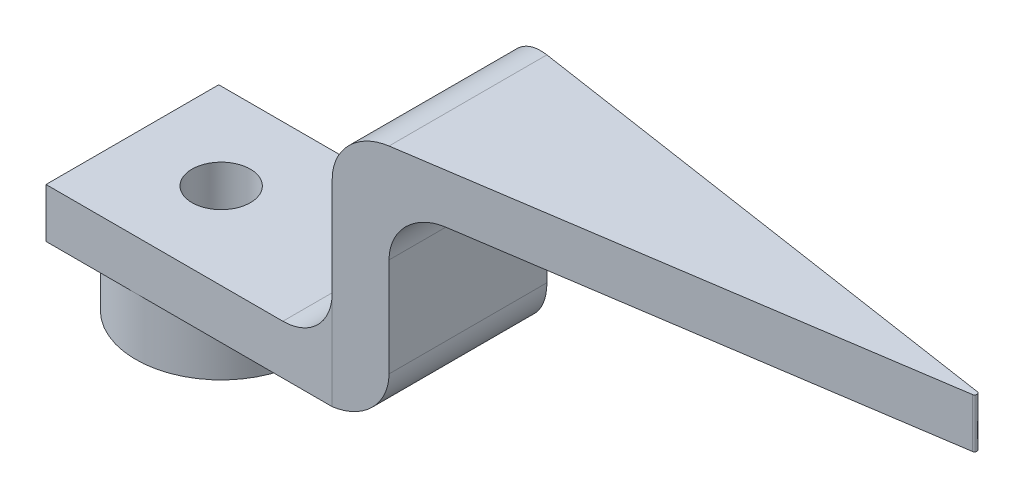
SolidWorks part; units mm, degrees
material "ABS"
ref_plane "Front Plane" through (0, 0, 0) normal (0, 0, 1) x (1, 0, 0)
ref_plane "Top Plane" through (0, 0, 0) normal (0, 1, 0) x (1, 0, 0)
ref_plane "Right Plane" through (0, 0, 0) normal (1, 0, 0) x (0, 0, -1)
sketch "Sketch1" plane through (0, 0, 0) normal (0, 0, 1) x (1, 0, 0)
  line L0 (39.624, 10.16) -> (12.7, 10.16)
  line L1 (12.7, 10.16) -> (12.7, 0)
  line L2 (12.7, 0) -> (0, 0)
  line L3 (0, 0) -> (-4.572, 0)
  dimension "D1" = 26.924
  dimension "D2" = 10.16
  dimension "D3" = 12.7
  dimension "D4" = 4.572
extrude "Extrude-Thin1" add sketch "Sketch1" along normal mid plane 8.89 thin
sketch "Sketch2" plane through (0, 12.7, 0) normal (0, 1, 0) x (1, 0, 0)
  line L0 (10.16, 4.445) -> (38.7916, 0.1256)
  line L3 (39.624, -4.445) -> (39.624, 4.445) construction
  line L5 (38.7916, -0.1256) -> (10.16, -4.445)
  line L6 (10.16, -4.445) -> (39.624, -4.445)
  line L7 (39.624, -4.445) -> (39.624, 4.445)
  line L8 (39.624, 4.445) -> (10.16, 4.445) construction
  line L9 (39.624, 4.445) -> (10.16, 4.445)
  arc A0 (38.7916, -0.1256) -> (38.7916, 0.1256) centre (38.7726, 0) ccw
  point P12 (39.624, 0)
  line M2 (39.624, 4.445) -> (10.16, 4.445)
  line M4 (10.16, -4.445) -> (39.624, -4.445)
  line M5 (39.624, -4.445) -> (39.624, 4.445)
  dimension "D1" = 0.127
extrude "Cut-Extrude1" cut sketch "Sketch2" against normal through all contours L5 M5 M4 | L0 M2 M5
fillet "Fillet1" radius 2.54 4 edges at (10.16, 2.54, 0) (12.7, 10.16, 0) (12.7, 0, 0) (10.16, 12.7, 0)
sketch "Sketch3" plane through (0, 2.54, 0) normal (0, 1, 0) x (1, 0, 0)
  circle A0 centre (0, 0) radius 1.5
  dimension "D1" = 3
extrude "Cut-Extrude2" cut sketch "Sketch3" against normal through all
sketch "Sketch4" plane through (0, 0, 0) normal (0, -1, 0) x (1, 0, 0)
  circle A0 centre (0, 0) radius 4.4
  dimension "D1" = 8.8
extrude "Boss-Extrude1" add sketch "Sketch4" along normal blind 3
sketch "Sketch5" plane through (0, -3, 0) normal (0, -1, 0) x (1, 0, 0)
  line L0 (0.1143, 2.4894) -> (0.0406, 2.3567)
  line L1 (0.0406, 2.3567) -> (-0.0406, 2.3567)
  line L2 (-0.0406, 2.3567) -> (-0.1143, 2.4894)
  line L3 (0, 2.3567) -> (0, 0) construction
  line L4 (0.3071, 2.3375) -> (0.2526, 2.4792)
  line L5 (0.3875, 2.3262) -> (0.3071, 2.3375)
  line L6 (0.4406, 2.4527) -> (0.3875, 2.3262)
  line L7 (0.6294, 2.2721) -> (0.5951, 2.4199)
  line L8 (0.7075, 2.2497) -> (0.6294, 2.2721)
  line L9 (0.7776, 2.3676) -> (0.7075, 2.2497)
  line L10 (0.9395, 2.1624) -> (0.9261, 2.3135)
  line L11 (1.0137, 2.1293) -> (0.9395, 2.1624)
  line L12 (1.0996, 2.2363) -> (1.0137, 2.1293)
  line L13 (1.2313, 2.0106) -> (1.2391, 2.1621)
  line L14 (1.3001, 1.9675) -> (1.2313, 2.0106)
  line L15 (1.4001, 2.0615) -> (1.3001, 1.9675)
  line L16 (1.4991, 1.8196) -> (1.5279, 1.9686)
  line L17 (1.5613, 1.7674) -> (1.4991, 1.8196)
  line L18 (1.6734, 1.8466) -> (1.5613, 1.7674)
  line L19 (1.7378, 1.5933) -> (1.7871, 1.7368)
  line L20 (1.7921, 1.5329) -> (1.7378, 1.5933)
  line L21 (1.9141, 1.5957) -> (1.7921, 1.5329)
  line L22 (1.9426, 1.3359) -> (2.0114, 1.4712)
  line L23 (1.988, 1.2686) -> (1.9426, 1.3359)
  line L24 (2.1175, 1.3138) -> (1.988, 1.2686)
  line L25 (2.1096, 1.0526) -> (2.1966, 1.1769)
  line L26 (2.1452, 0.9796) -> (2.1096, 1.0526)
  line L27 (2.2798, 1.0063) -> (2.1452, 0.9796)
  line L28 (2.2356, 0.7487) -> (2.339, 0.8598)
  line L29 (2.2607, 0.6715) -> (2.2356, 0.7487)
  line L30 (2.3976, 0.6792) -> (2.2607, 0.6715)
  line L31 (2.318, 0.4303) -> (2.4359, 0.5259)
  line L32 (2.3321, 0.3503) -> (2.318, 0.4303)
  line L33 (2.4688, 0.3389) -> (2.3321, 0.3503)
  line L34 (2.3554, 0.1035) -> (2.4854, 0.1818)
  line L35 (2.3582, 0.0224) -> (2.3554, 0.1035)
  line L36 (2.492, -0.008) -> (2.3582, 0.0224)
  line L37 (2.3468, -0.2253) -> (2.4865, -0.1659)
  line L38 (2.3383, -0.3061) -> (2.3468, -0.2253)
  line L39 (2.4666, -0.3547) -> (2.3383, -0.3061)
  line L40 (2.2926, -0.5497) -> (2.4392, -0.5103)
  line L41 (2.273, -0.6285) -> (2.2926, -0.5497)
  line L42 (2.3933, -0.6945) -> (2.273, -0.6285)
  line L43 (2.1938, -0.8634) -> (2.3444, -0.8448)
  line L44 (2.1634, -0.9387) -> (2.1938, -0.8634)
  line L45 (2.2733, -1.0209) -> (2.1634, -0.9387)
  line L46 (2.0523, -1.1604) -> (2.204, -1.1629)
  line L47 (2.0117, -1.2307) -> (2.0523, -1.1604)
  line L48 (2.1091, -1.3273) -> (2.0117, -1.2307)
  line L49 (1.8708, -1.4347) -> (2.0207, -1.4583)
  line L50 (1.8208, -1.4987) -> (1.8708, -1.4347)
  line L51 (1.9039, -1.6079) -> (1.8208, -1.4987)
  line L52 (1.6808, -1.6542) -> (1.7981, -1.7254)
  line L53 (1.6224, -1.7106) -> (1.6808, -1.6542)
  line L54 (1.6615, -1.8572) -> (1.6224, -1.7106)
  line L55 (1.4342, -1.872) -> (1.5405, -1.9588)
  line L56 (1.3685, -1.9198) -> (1.4342, -1.872)
  line L57 (1.3869, -2.0704) -> (1.3685, -1.9198)
  line L58 (1.1597, -2.0534) -> (1.2529, -2.1541)
  line L59 (1.088, -2.0916) -> (1.1597, -2.0534)
  line L60 (1.0853, -2.2433) -> (1.088, -2.0916)
  line L61 (0.8627, -2.1948) -> (0.9409, -2.3075)
  line L62 (0.7863, -2.2226) -> (0.8627, -2.1948)
  line L63 (0.7625, -2.3725) -> (0.7863, -2.2226)
  line L64 (0.5488, -2.2935) -> (0.6106, -2.416)
  line L65 (0.4694, -2.3104) -> (0.5488, -2.2935)
  line L66 (0.4249, -2.4555) -> (0.4694, -2.3104)
  line L67 (0.2243, -2.3476) -> (0.2684, -2.4775)
  line L68 (0.1433, -2.3533) -> (0.2243, -2.3476)
  line L69 (0.079, -2.4907) -> (0.1433, -2.3533)
  line L70 (-0.1046, -2.356) -> (-0.079, -2.4907)
  line L71 (-0.1857, -2.3503) -> (-0.1046, -2.356)
  line L72 (-0.2684, -2.4775) -> (-0.1857, -2.3503)
  line L73 (-0.4315, -2.3185) -> (-0.4249, -2.4555)
  line L74 (-0.5109, -2.3016) -> (-0.4315, -2.3185)
  line L75 (-0.6106, -2.416) -> (-0.5109, -2.3016)
  line L76 (-0.75, -2.2359) -> (-0.7625, -2.3725)
  line L77 (-0.8263, -2.2081) -> (-0.75, -2.2359)
  line L78 (-0.9409, -2.3075) -> (-0.8263, -2.2081)
  line L79 (-1.0539, -2.1097) -> (-1.0853, -2.2433)
  line L80 (-1.1256, -2.0716) -> (-1.0539, -2.1097)
  line L81 (-1.2529, -2.1541) -> (-1.1256, -2.0716)
  line L82 (-1.3372, -1.9425) -> (-1.3869, -2.0704)
  line L83 (-1.4029, -1.8948) -> (-1.3372, -1.9425)
  line L84 (-1.5405, -1.9588) -> (-1.4029, -1.8948)
  line L85 (-1.6224, -1.7106) -> (-1.6615, -1.8572)
  line L86 (-1.6808, -1.6542) -> (-1.6224, -1.7106)
  line L87 (-1.826, -1.6985) -> (-1.6808, -1.6542)
  line L88 (-1.8208, -1.4987) -> (-1.9039, -1.6079)
  line L89 (-1.8708, -1.4347) -> (-1.8208, -1.4987)
  line L90 (-2.0207, -1.4583) -> (-1.8708, -1.4347)
  line L91 (-2.0117, -1.2307) -> (-2.1091, -1.3273)
  line L92 (-2.0523, -1.1604) -> (-2.0117, -1.2307)
  line L93 (-2.204, -1.1629) -> (-2.0523, -1.1604)
  line L94 (-2.1634, -0.9387) -> (-2.2733, -1.0209)
  line L95 (-2.1938, -0.8634) -> (-2.1634, -0.9387)
  line L96 (-2.3444, -0.8448) -> (-2.1938, -0.8634)
  line L97 (-2.273, -0.6285) -> (-2.3933, -0.6945)
  line L98 (-2.2926, -0.5497) -> (-2.273, -0.6285)
  line L99 (-2.4392, -0.5103) -> (-2.2926, -0.5497)
  line L100 (-2.3383, -0.3061) -> (-2.4666, -0.3547)
  line L101 (-2.3468, -0.2253) -> (-2.3383, -0.3061)
  line L102 (-2.4865, -0.1659) -> (-2.3468, -0.2253)
  line L103 (-2.3568, 0.061) -> (-2.492, -0.008)
  line L104 (-2.3554, 0.1035) -> (-2.3568, 0.061)
  line L105 (-2.4854, 0.1818) -> (-2.3554, 0.1035)
  line L106 (-2.3254, 0.3884) -> (-2.4688, 0.3389)
  line L107 (-2.318, 0.4303) -> (-2.3254, 0.3884)
  line L108 (-2.4359, 0.5259) -> (-2.318, 0.4303)
  line L109 (-2.2487, 0.7083) -> (-2.3976, 0.6792)
  line L110 (-2.2356, 0.7487) -> (-2.2487, 0.7083)
  line L111 (-2.339, 0.8598) -> (-2.2356, 0.7487)
  line L112 (-2.1283, 1.0144) -> (-2.2798, 1.0063)
  line L113 (-2.1096, 1.0526) -> (-2.1283, 1.0144)
  line L114 (-2.1966, 1.1769) -> (-2.1096, 1.0526)
  line L115 (-1.9664, 1.3007) -> (-2.1175, 1.3138)
  line L116 (-1.9426, 1.3359) -> (-1.9664, 1.3007)
  line L117 (-2.0114, 1.4712) -> (-1.9426, 1.3359)
  line L118 (-1.7662, 1.5617) -> (-1.9141, 1.5957)
  line L119 (-1.7378, 1.5933) -> (-1.7662, 1.5617)
  line L120 (-1.7871, 1.7368) -> (-1.7378, 1.5933)
  line L121 (-1.5317, 1.7923) -> (-1.6734, 1.8466)
  line L122 (-1.4991, 1.8196) -> (-1.5317, 1.7923)
  line L123 (-1.5279, 1.9686) -> (-1.4991, 1.8196)
  line L124 (-1.2673, 1.988) -> (-1.4001, 2.0615)
  line L125 (-1.2313, 2.0106) -> (-1.2673, 1.988)
  line L126 (-1.2391, 2.1621) -> (-1.2313, 2.0106)
  line L127 (-0.9783, 2.1451) -> (-1.0996, 2.2363)
  line L128 (-0.9041, 2.1781) -> (-0.9783, 2.1451)
  line L129 (-0.9261, 2.3135) -> (-0.9041, 2.1781)
  line L130 (-0.6703, 2.2603) -> (-0.7776, 2.3676)
  line L131 (-0.5922, 2.2827) -> (-0.6703, 2.2603)
  line L132 (-0.5951, 2.4199) -> (-0.5922, 2.2827)
  line L133 (-0.3492, 2.3316) -> (-0.4406, 2.4527)
  line L134 (-0.2687, 2.3429) -> (-0.3492, 2.3316)
  line L135 (-0.2526, 2.4792) -> (-0.2687, 2.3429)
  arc A0 (-2.2798, 1.0063) -> (-2.339, 0.8598) centre (0, 0) ccw
  arc A1 (-2.3976, 0.6792) -> (-2.4359, 0.5259) centre (0, 0) ccw
  arc A2 (-2.4688, 0.3389) -> (-2.4854, 0.1818) centre (0, 0) ccw
  arc A3 (-2.492, -0.008) -> (-2.4865, -0.1659) centre (0, 0) ccw
  arc A4 (-2.4666, -0.3547) -> (-2.4392, -0.5103) centre (0, 0) ccw
  arc A5 (-2.3933, -0.6945) -> (-2.3444, -0.8448) centre (0, 0) ccw
  arc A6 (-2.2733, -1.0209) -> (-2.204, -1.1629) centre (0, 0) ccw
  arc A7 (-2.1091, -1.3273) -> (-2.0207, -1.4583) centre (0, 0) ccw
  arc A8 (-1.9039, -1.6079) -> (-1.8241, -1.6979) centre (0, 0) ccw
  arc A9 (-1.3869, -2.0704) -> (-1.2529, -2.1541) centre (0, 0) ccw
  arc A10 (-1.0853, -2.2433) -> (-0.9409, -2.3075) centre (0, 0) ccw
  arc A11 (-0.7625, -2.3725) -> (-0.6106, -2.416) centre (0, 0) ccw
  arc A12 (-0.4249, -2.4555) -> (-0.2684, -2.4775) centre (0, 0) ccw
  arc A13 (-0.079, -2.4907) -> (0.079, -2.4907) centre (0, 0) ccw
  arc A14 (0.2684, -2.4775) -> (0.4249, -2.4555) centre (0, 0) ccw
  arc A15 (0.9409, -2.3075) -> (1.0853, -2.2433) centre (0, 0) ccw
  arc A16 (0.6106, -2.416) -> (0.7625, -2.3725) centre (0, 0) ccw
  arc A17 (1.2529, -2.1541) -> (1.3869, -2.0704) centre (0, 0) ccw
  arc A18 (1.5405, -1.9588) -> (1.6615, -1.8572) centre (0, 0) ccw
  arc A19 (1.7981, -1.7254) -> (1.9039, -1.6079) centre (0, 0) ccw
  arc A20 (2.0207, -1.4583) -> (2.1091, -1.3273) centre (0, 0) ccw
  arc A21 (2.204, -1.1629) -> (2.2733, -1.0209) centre (0, 0) ccw
  arc A22 (2.3444, -0.8448) -> (2.3933, -0.6945) centre (0, 0) ccw
  arc A23 (2.4392, -0.5103) -> (2.4666, -0.3547) centre (0, 0) ccw
  arc A24 (2.4865, -0.1659) -> (2.492, -0.008) centre (0, 0) ccw
  arc A25 (2.4854, 0.1818) -> (2.4688, 0.3389) centre (0, 0) ccw
  arc A26 (2.4359, 0.5259) -> (2.3976, 0.6792) centre (0, 0) ccw
  arc A27 (2.339, 0.8598) -> (2.2798, 1.0063) centre (0, 0) ccw
  arc A28 (2.1966, 1.1769) -> (2.1175, 1.3138) centre (0, 0) ccw
  arc A29 (2.0114, 1.4712) -> (1.9141, 1.5957) centre (0, 0) ccw
  arc A30 (1.7871, 1.7368) -> (1.6734, 1.8466) centre (0, 0) ccw
  arc A31 (1.5279, 1.9686) -> (1.4001, 2.0615) centre (0, 0) ccw
  arc A32 (1.2391, 2.1621) -> (1.0996, 2.2363) centre (0, 0) ccw
  arc A33 (0.9261, 2.3135) -> (0.7776, 2.3676) centre (0, 0) ccw
  arc A34 (0.5951, 2.4199) -> (0.4406, 2.4527) centre (0, 0) ccw
  arc A35 (0.2526, 2.4792) -> (0.1143, 2.4894) centre (0, 0) ccw
  arc A36 (-0.1143, 2.4894) -> (-0.2526, 2.4792) centre (0, 0) ccw
  arc A37 (-0.4406, 2.4527) -> (-0.5951, 2.4199) centre (0, 0) ccw
  arc A38 (-2.1175, 1.3138) -> (-2.1966, 1.1769) centre (0, 0) ccw
  arc A39 (-1.9141, 1.5957) -> (-2.0114, 1.4712) centre (0, 0) ccw
  arc A40 (-1.6734, 1.8466) -> (-1.7871, 1.7368) centre (0, 0) ccw
  arc A41 (-1.4001, 2.0615) -> (-1.5279, 1.9686) centre (0, 0) ccw
  arc A42 (-1.0996, 2.2363) -> (-1.2391, 2.1621) centre (0, 0) ccw
  arc A43 (-0.7776, 2.3676) -> (-0.9261, 2.3135) centre (0, 0) ccw
  arc A44 (-1.6615, -1.8572) -> (-1.5405, -1.9588) centre (0, 0) ccw
  point P187 (0, 0)
  dimension "D1" = 4.984
  dimension "D2" = 0.1517
  dimension "D3" = 0.0812
  dimension "D4" = 0.1327
extrude "Cut-Extrude3" cut sketch "Sketch5" against normal up to surface (3 mm away) contours L130 A43 L129 L128 L127 A42 L126 L125 L124 A41 L123 L122 L121 A40 L120 L119 L118 A39 L117 L116 L115 A38 L114 L113 L112 A0 L111 L110 L109 A1 L108 L107 L106 A2 L105 L104 L103 A3 L102 L101 L100 A4 L99 L98 L97 A5 L96 L95 L94 A6 L93
